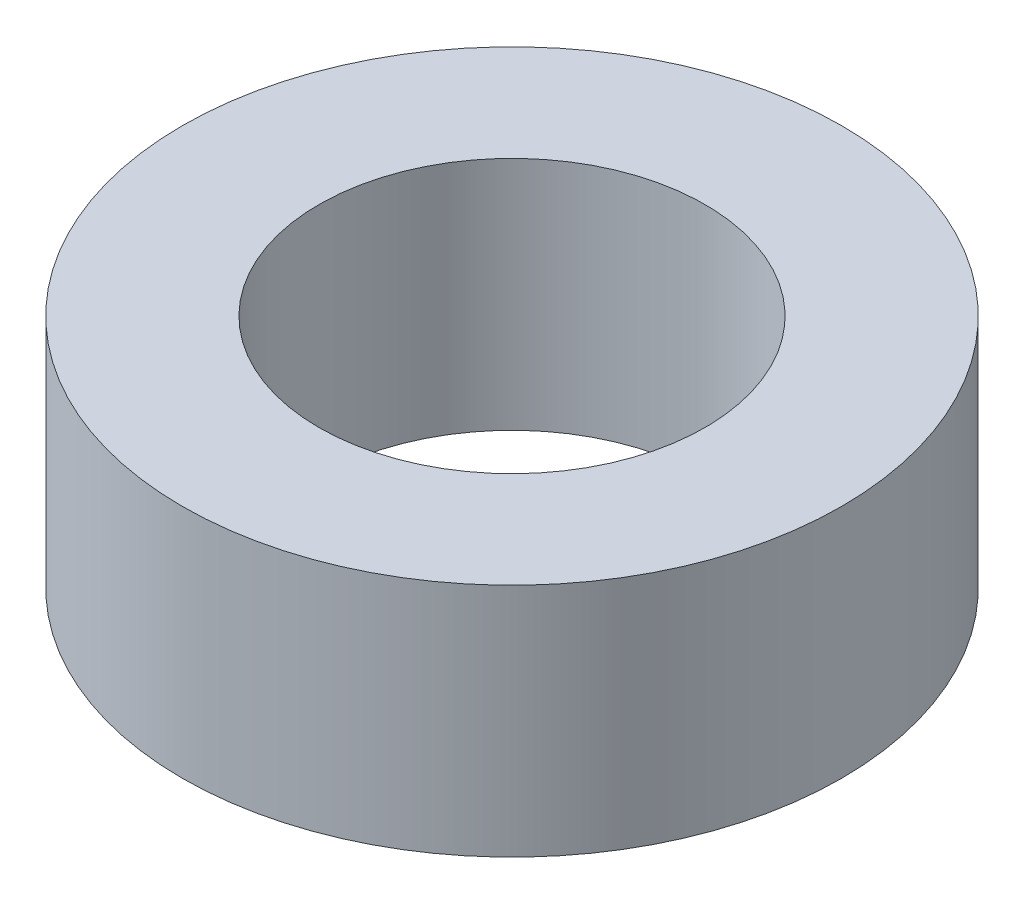
SolidWorks part; units mm, degrees
ref_plane "前视" through (0, 0, 0) normal (0, 0, 1) x (1, 0, 0)
ref_plane "上视" through (0, 0, 0) normal (0, 1, 0) x (1, 0, 0)
ref_plane "右视" through (0, 0, 0) normal (1, 0, 0) x (0, 0, -1)
sketch "草图1" plane through (0, 0, 0) normal (0, 1, 0) x (1, 0, 0)
  circle A0 centre (0, 0) radius 7
  circle A1 centre (0, 0) radius 4.1
  dimension "D1" = 8.2
  dimension "D2" = 14
extrude "凸台-拉伸1" add sketch "草图1" along normal blind 5
